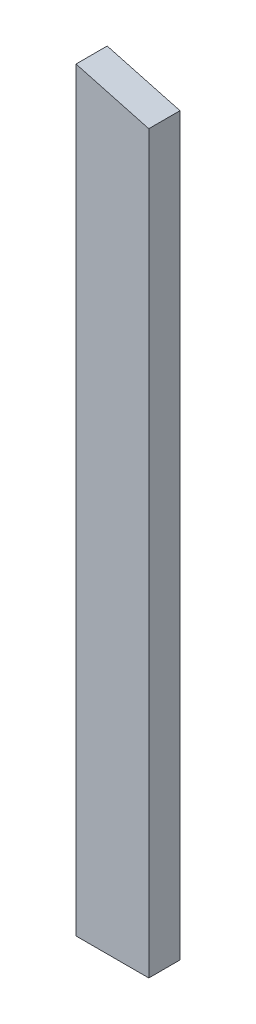
SolidWorks part; units mm, degrees
material "Pine"
ref_plane "Front Plane" through (0, 0, 0) normal (0, 0, 1) x (1, 0, 0)
ref_plane "Top Plane" through (0, 0, 0) normal (0, 1, 0) x (1, 0, 0)
ref_plane "Right Plane" through (0, 0, 0) normal (1, 0, 0) x (0, 0, -1)
sketch "Sketch1" plane through (0, 0, 0) normal (0, 0, 1) x (1, 0, 0)
  line L0 (-108.5345, -3.9032) -> (-108.5345, 1464.0363)
  line L1 (-641.9345, -3.9032) -> (-641.9345, 1464.0363)
  line L2 (-870.5345, -3.9032) -> (-870.5345, 625.8363)
  line L3 (-972.1345, 737.9573) -> (-972.1345, 834.2968)
  line L4 (-768.9345, 834.2968) -> (-768.9345, 986.6968)
  line L5 (-972.1345, 834.2968) -> (-768.9345, 834.2968)
  line L6 (-528.0858, 1843.9468) -> (-737.1845, 1843.9468)
  line L7 (-968.4148, 728.977) -> (-874.2542, 634.8165)
  line L8 (-737.1845, 1672.0154) -> (-737.1845, 1762.6932)
  line L9 (-520.195, 1875.6968) -> (-756.2345, 1875.6968)
  line L10 (-112.2542, 1473.0165) -> (-511.2148, 1871.977)
  line L11 (-737.1845, 1692.941) -> (-241.631, 1467.6894)
  line L12 (-596.8655, 1608.234) -> (-737.1845, 983.1768)
  line L13 (-763.9746, 985.3593) -> (-224.4471, 839.8687)
  line L14 (-761.4898, 1669.1128) -> (-638.6318, 1613.2683)
  line L15 (-631.4955, 1598.9249) -> (-768.9345, 986.6968)
  line L16 (-768.9345, 1680.6745) -> (-768.9345, 1862.9968)
  line L17 (-737.1845, 1780.4468) -> (-737.1845, 1843.9468)
  line L18 (-737.1845, 1692.941) -> (-737.1845, 1843.9468) construction
  line L19 (-737.1845, 1692.941) -> (-737.1845, 1762.6932) construction
  line L20 (-838.7845, -3.9032) -> (-838.7845, 834.2968)
  line L21 (-745.0674, 1675.5986) -> (-249.5139, 1450.347) construction
  line L22 (-140.2845, -3.9032) -> (-140.2845, 1456.1455)
  line L23 (-140.2845, 1456.1455) -> (-528.0858, 1843.9468)
  line L24 (-537.8111, 1581.3911) -> (-673.6845, 976.1369)
  line L25 (-768.9345, 966.9663) -> (-229.407, 821.4757)
  line L26 (-737.1845, 1672.0154) -> (-203.7845, 1429.5608)
  line L27 (-528.0858, 1843.9468) -> (-554.3883, 1780.4468)
  line L28 (-140.2845, 1456.1455) -> (-203.7845, 1429.8429)
  line L29 (-775.2845, -3.9032) -> (-775.2845, 834.2968)
  line L30 (-773.8944, 968.3038) -> (-229.407, 821.4757) construction
  line L31 (-203.7845, -3.9032) -> (-203.7845, 1429.8429)
  line L32 (-203.7845, 1429.8429) -> (-554.3883, 1780.4468)
  line L33 (-554.3883, 1780.4468) -> (-737.1845, 1780.4468)
  line L34 (-768.9345, 966.9663) -> (-763.9746, 985.3593)
  line L35 (-737.1845, 1762.6932) -> (-369.5099, 1595.5683)
  line L36 (-673.6845, 1733.8295) -> (-599.2171, 1699.9807) construction
  line L37 (-737.1845, 1692.941) -> (-625.4936, 1642.1724) construction
  line L38 (-538.5586, 1578.0615) -> (-673.6845, 976.1369) construction
  line L39 (-600.5166, 1591.9704) -> (-737.1845, 983.1768) construction
  line L40 (-554.3883, 1780.4468) -> (-673.6845, 1780.4468) construction
  line L41 (-203.7845, 91.3468) -> (-203.7845, 1429.8429) construction
  line L42 (-140.2845, 27.8468) -> (-140.2845, 1456.1455) construction
  line L43 (-775.2845, 91.3468) -> (-775.2845, 625.8363) construction
  line L44 (-838.7845, 27.8468) -> (-838.7845, 625.8363) construction
  line L45 (-203.7845, 91.3468) -> (-775.2845, 91.3468) construction
  line L46 (-140.2845, 27.8468) -> (-838.7845, 27.8468) construction
  line L47 (-940.3845, 745.8481) -> (-851.8036, 657.2672) construction
  line L48 (-843.7807, 739.0468) -> (-806.9023, 702.1685) construction
  line L49 (-843.7807, 739.0468) -> (-673.6845, 739.0468) construction
  line L50 (-940.3845, 802.5468) -> (-737.1845, 802.5468) construction
  line L51 (-940.3845, 745.8481) -> (-940.3845, 802.5468) construction
  line L52 (-843.7807, 739.0468) -> (-843.7807, 739.0468) construction
  line L53 (-673.6845, 1733.8295) -> (-673.6845, 1780.4468) construction
  line L54 (-756.2345, 1692.941) -> (-756.2345, 1792.2779) construction
  line L55 (-756.2345, 1792.2779) -> (-361.627, 1612.9108) construction
  line L56 (-673.6845, 739.0468) -> (-673.6845, 976.1369) construction
  line L57 (-737.1845, 802.5468) -> (-737.1845, 983.1768) construction
  line L58 (-768.9345, 986.6968) -> (-224.4471, 839.8687) construction
  line L59 (-224.4471, 839.8687) -> (-229.407, 821.4757)
  line L60 (-730.8345, -3.9032) -> (-730.8345, 1464.0363)
  line L63 (-108.5345, -3.9032) -> (-248.0476, -3.9032)
  line L68 (-108.5345, -3.9032) -> (-870.5345, -3.9032) construction
  line L69 (-108.5345, -3.9032) -> (-870.5345, -3.9032)
  line L72 (-108.5345, 34.1968) -> (-870.5345, 34.1968)
  arc A0 (-108.5345, 1464.0363) -> (-112.2542, 1473.0165) centre (-121.2345, 1464.0363) ccw
  arc A1 (-511.2148, 1871.977) -> (-520.195, 1875.6968) centre (-520.195, 1862.9968) ccw
  arc A2 (-768.9345, 1862.9968) -> (-756.2345, 1875.6968) centre (-756.2345, 1862.9968) cw
  arc A3 (-768.9345, 1680.6745) -> (-761.4898, 1669.1128) centre (-756.2345, 1680.6745) ccw
  arc A4 (-631.4955, 1598.9249) -> (-638.6318, 1613.2683) centre (-643.8871, 1601.7067) ccw
  arc A5 (-972.1345, 737.9573) -> (-968.4148, 728.977) centre (-959.4345, 737.9573) ccw
  arc A6 (-870.5345, 625.8363) -> (-874.2542, 634.8165) centre (-883.2345, 625.8363) ccw
  arc A7 (-737.1845, 1843.9468) -> (-737.1845, 1843.9468) centre (-737.1845, 1843.9468) cw
  arc A8 (-737.1845, 1692.941) -> (-737.1845, 1692.941) centre (-737.1845, 1692.941) ccw
  arc A12 (-140.2845, 1456.1455) -> (-140.2845, 1456.1455) centre (-140.2845, 1456.1455) ccw
  arc A13 (-528.0858, 1843.9468) -> (-528.0858, 1843.9468) centre (-528.0858, 1843.9468) ccw
  arc A14 (-600.5166, 1591.9704) -> (-625.4936, 1642.1724) centre (-643.8871, 1601.7067) ccw construction
  arc A16 (-203.7845, 1429.8429) -> (-203.7845, 1429.8429) centre (-203.7845, 1429.8429) ccw
  arc A17 (-554.3883, 1780.4468) -> (-554.3883, 1780.4468) centre (-554.3883, 1780.4468) ccw
  arc A18 (-673.6845, 1780.4468) -> (-673.6845, 1780.4468) centre (-673.6845, 1780.4468) cw
  arc A19 (-673.6845, 1733.8295) -> (-673.6845, 1733.8295) centre (-673.6845, 1733.8295) ccw
  arc A20 (-838.7845, 625.8363) -> (-851.8036, 657.2672) centre (-883.2345, 625.8363) ccw construction
  arc A21 (-775.2845, 625.8363) -> (-806.9023, 702.1685) centre (-883.2345, 625.8363) ccw construction
  arc A22 (-843.7807, 739.0468) -> (-843.7807, 739.0468) centre (-843.7807, 739.0468) ccw construction
  arc A23 (-940.3845, 745.8481) -> (-940.3845, 745.8481) centre (-940.3845, 745.8481) ccw construction
  arc A24 (-756.2345, 1692.941) -> (-745.0674, 1675.5986) centre (-737.1845, 1692.941) ccw construction
  dimension "D1" = 12.7
  dimension "D7" = 88.9
  dimension "D6" = 533.4
  dimension "D2" = 31.75
  dimension "D3" = 63.5
  dimension "D4" = 19.05
  dimension "D5" = 19.05
  dimension "D8" = 38.1
extrude "Boss-Extrude1" add sketch "Sketch1" along normal blind 38.1
